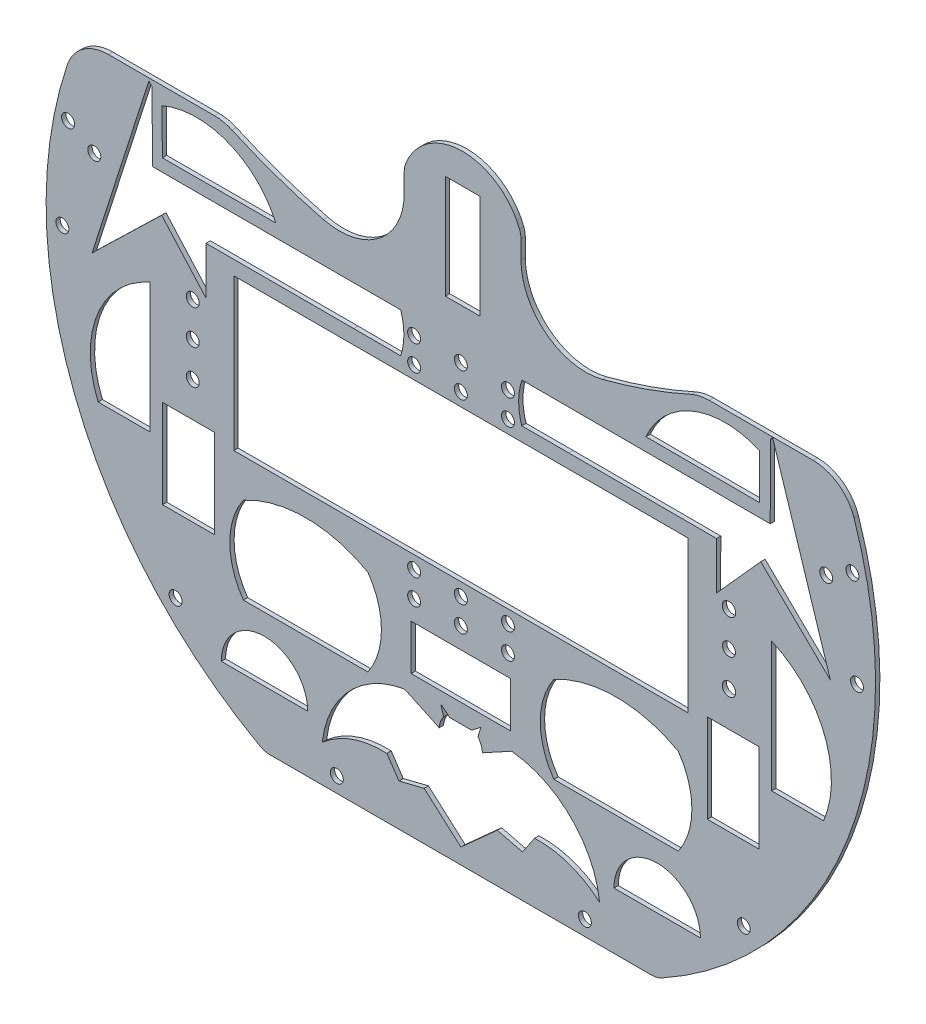
SolidWorks part; units mm, degrees
ref_plane "Alzado" through (0, 0, 0) normal (0, 0, 1) x (1, 0, 0)
ref_plane "Planta" through (0, 0, 0) normal (0, 1, 0) x (1, 0, 0)
ref_plane "Vista lateral" through (0, 0, 0) normal (1, 0, 0) x (0, 0, -1)
sketch "Croquis1" plane through (0, 0, 0) normal (0, 0, 1) x (1, 0, 0)
  line L6 (309.5147, 61.7075) -> (309.5147, 57.3276)
  line L7 (336.5145, 61.7075) -> (336.5145, 57.5364)
  line L8 (253.593, 36.515) -> (253.4846, 46.9134)
  line L9 (251.233, 49.5222) -> (250.4719, 50.3729)
  line L10 (253.593, 36.515) -> (279.8125, 36.577)
  line L11 (394.2079, 50.4438) -> (394.7077, 51.0653)
  line L12 (265.656, 50.9799) -> (241.0817, 50.9799)
  line L13 (391.6231, 36.515) -> (391.7315, 46.9134)
  line L14 (391.6231, 36.515) -> (365.4036, 36.577)
  line L15 (380.0087, 51.1814) -> (404.0672, 51.1814)
  line L111 (253.6081, -32.9371) -> (259.6081, -32.9371)
  line L112 (259.6081, -32.9371) -> (265.6081, -32.9371)
  line L113 (265.6081, -32.9371) -> (265.6081, -12.4371)
  line L114 (265.6081, -12.4371) -> (253.6081, -12.4371)
  line L115 (253.6081, -12.4371) -> (253.6081, -32.9371)
  line L116 (391.6081, -22.6871) -> (391.6081, -12.4371)
  line L117 (391.6081, -22.6871) -> (391.6081, -32.9371)
  line L118 (391.6081, -32.9371) -> (379.6081, -32.9371)
  line L119 (379.6081, -32.9371) -> (379.6081, -12.4371)
  line L120 (379.6081, -12.4371) -> (391.6081, -12.4371)
  line L121 (311.1081, -38.0079) -> (334.1081, -38.0079)
  line L122 (327.0147, 41.5355) -> (327.0147, 65.5355)
  line L123 (327.0147, 65.5355) -> (319.0147, 65.5355)
  line L124 (319.0147, 65.5355) -> (319.0147, 41.5355)
  line L125 (283.6081, 21.1487) -> (361.6081, 21.1487)
  line L126 (319.0147, 41.5355) -> (327.0147, 41.5355)
  line L127 (283.6081, 21.1487) -> (272.6081, 21.1487)
  line L128 (361.6081, 21.1487) -> (372.6081, 21.1487)
  line L129 (272.6081, 21.1487) -> (272.3081, 21.1487)
  line L132 (372.9081, -42.6871) -> (344.1081, -42.6871)
  line L133 (301.1081, -42.6871) -> (272.3081, -42.6871)
  line L136 (372.9081, -13.8513) -> (375.1081, -13.8513)
  line L137 (375.1081, -13.8513) -> (375.1081, 21.1487)
  line L138 (372.6081, 21.1487) -> (375.1081, 21.1487)
  line L139 (272.3081, -13.8513) -> (270.1081, -13.8513)
  line L140 (270.1081, -13.8513) -> (270.1081, 21.1487)
  line L141 (270.1081, 21.1487) -> (272.6081, 21.1487)
  line L142 (311.1081, -27.5079) -> (311.1081, -38.0079)
  line L143 (334.1081, -27.5079) -> (334.1081, -38.0079)
  line L144 (270.1081, -13.8513) -> (270.1081, 21.1487)
  line L147 (272.3081, -13.8513) -> (372.9081, -13.8513)
  line L148 (311.1081, -27.5079) -> (334.1081, -27.5079)
  line L149 (322.6081, -67.0079) -> (314.1156, -59.4845)
  line L150 (322.6081, -67.0079) -> (331.0395, -59.4162)
  line L151 (331.0395, -59.4162) -> (336.8613, -60.8677)
  line L152 (336.8613, -60.8677) -> (339.6572, -56.7225)
  line L153 (308.2939, -60.936) -> (305.4979, -56.7908)
  line L154 (322.6081, -42.3598) -> (320.1081, -42.3598)
  line L155 (322.6081, -42.3598) -> (325.1081, -42.3598)
  line L156 (325.1081, -42.3598) -> (327.2548, -40.6826)
  line L157 (327.2548, -40.6826) -> (326.5733, -42.9116)
  line L158 (327.2548, -40.6826) -> (326.5711, -42.9186)
  line L159 (320.1081, -42.3598) -> (317.9614, -40.6826)
  line L160 (317.9614, -40.6826) -> (318.6428, -42.9116)
  line L161 (317.9614, -40.6826) -> (318.645, -42.9186)
  line L162 (317.6081, -45.6294) -> (309.5758, -41.866)
  line L163 (327.6081, -45.6294) -> (334.3613, -41.9345)
  line L164 (314.1156, -59.4845) -> (308.2939, -60.936)
  line L165 (251.233, 49.5222) -> (251.2592, 33.6206)
  line L166 (297.8512, 24.4503) -> (263.6769, 24.4503)
  line L167 (263.6769, 24.4503) -> (263.6769, 13.4789)
  line L168 (263.6769, 13.4789) -> (253.4246, 24.9379)
  line L169 (253.4246, 24.9379) -> (237.3248, 9.3342)
  line L170 (237.3248, 9.3342) -> (250.4719, 50.3729)
  line L171 (297.8353, 33.6206) -> (251.2592, 33.6206)
  line L172 (308.7015, 24.4226) -> (297.8512, 24.4503)
  line L173 (297.8353, 33.6206) -> (308.7015, 33.6206)
  line L174 (394.2079, 50.4438) -> (394.1514, 33.5004)
  line L175 (347.5441, 24.4085) -> (381.7183, 24.351)
  line L176 (381.7183, 24.351) -> (381.6999, 13.3796)
  line L177 (381.6999, 13.3796) -> (391.9714, 24.8213)
  line L178 (391.9714, 24.8213) -> (408.0449, 9.1905)
  line L179 (408.0449, 9.1905) -> (394.7077, 51.0653)
  line L180 (347.5754, 33.5788) -> (394.1514, 33.5004)
  line L181 (336.6937, 24.399) -> (347.5441, 24.4085)
  line L182 (347.5754, 33.5788) -> (336.7092, 33.5971)
  line L183 (267.2015, -57.5079) -> (287.2015, -57.5079)
  line L184 (378.0147, -57.5079) -> (358.0147, -57.5079)
  line L185 (293.9244, -70.6013) -> (366.6962, -70.6013)
  line L186 (293.9244, -70.6013) -> (278.52, -70.6013)
  line L187 (394.4844, -19.815) -> (406.4844, -19.815)
  line L188 (394.4844, -19.815) -> (394.4844, 10.185)
  line L189 (250.7317, -19.815) -> (238.7317, -19.815)
  line L190 (250.7317, -19.815) -> (250.7317, 10.185)
  arc A2 (309.8507, 63.5097) -> (336.1785, 63.5097) centre (323.0146, 58.4231) cw
  arc A8 (269.7373, 50.1091) -> (290.8357, 42.7857) centre (322.6081, 168.3733) ccw
  arc A9 (355.2999, 43.0219) -> (375.8953, 50.2962) centre (322.6081, 168.3733) ccw
  arc A10 (336.5145, 57.5364) -> (355.2999, 43.0219) centre (351.5145, 57.5364) ccw
  arc A11 (309.5147, 57.3276) -> (290.8357, 42.7857) centre (294.5147, 57.3276) cw
  arc A12 (365.4036, 36.577) -> (391.7315, 46.9134) centre (383.7357, 28.5812) cw
  arc A13 (279.8125, 36.577) -> (253.4846, 46.9134) centre (261.4804, 28.5812) ccw
  arc A16 (369.1211, -69.9739) -> (366.6962, -70.6013) centre (366.6962, -65.6013) cw
  arc A17 (278.52, -70.6013) -> (276.0951, -69.9739) centre (278.52, -65.6013) cw
  arc A18 (336.1785, 63.5097) -> (336.5145, 61.7075) centre (331.5145, 61.7075) cw
  arc A19 (309.8507, 63.5097) -> (309.5147, 61.7075) centre (314.5147, 61.7075) ccw
  arc A22 (269.7373, 50.1091) -> (265.656, 50.9799) centre (265.656, 40.9799) ccw
  arc A23 (380.0087, 51.1814) -> (375.8953, 50.2962) centre (380.0087, 41.1814) ccw
  arc A24 (413.5495, 44.3573) -> (404.0672, 51.1814) centre (404.0672, 41.1814) ccw
  arc A25 (241.0817, 50.9799) -> (231.5915, 44.1323) centre (241.0817, 40.9799) ccw
  circle A159 centre (333.5054, 29.9987) radius 1.5
  circle A164 centre (384.6081, -4.3513) radius 1.55
  circle A165 centre (384.6081, 11.6487) radius 1.55
  circle A166 centre (293.9244, -67.1013) radius 1.5
  circle A167 centre (351.292, -67.1013) radius 1.5
  circle A168 centre (237.8501, 29.5597) radius 1.5
  circle A169 centre (407.0983, 29.6722) radius 1.5
  arc A170 (231.5915, 44.1323) -> (276.0951, -69.9739) centre (322.6081, 13.8987) ccw
  arc A171 (369.1211, -69.9739) -> (413.5495, 44.3573) centre (322.6081, 13.8987) ccw
  circle A176 centre (311.8064, 29.9987) radius 1.5
  circle A177 centre (260.6081, 11.6487) radius 1.5
  circle A178 centre (260.6081, -4.3513) radius 1.5
  circle A179 centre (260.6081, 3.6487) radius 1.5
  circle A180 centre (384.6081, 3.6487) radius 1.5
  circle A182 centre (231.7879, 33.0597) radius 1.5
  circle A184 centre (413.1604, 33.1722) radius 1.5
  circle A185 centre (414.2216, 11.3987) radius 1.5
  circle A186 centre (256.6409, -50.1013) radius 1.5
  circle A187 centre (388.037, -50.1013) radius 1.5
  circle A188 centre (322.6081, 29.9987) radius 1.5
  circle A189 centre (311.8064, -22.7013) radius 1.5
  circle A190 centre (322.6081, -22.7013) radius 1.5
  circle A191 centre (333.5054, -22.7013) radius 1.5
  circle A192 centre (322.6081, -16.8513) radius 1.5
  circle A193 centre (311.8064, -16.8513) radius 1.5
  circle A194 centre (333.5054, -16.8513) radius 1.5
  circle A195 centre (311.8064, 24.1487) radius 1.5
  circle A196 centre (322.6081, 24.1487) radius 1.5
  circle A197 centre (333.5054, 24.1487) radius 1.5
  arc A204 (354.7015, -62.0505) -> (334.3613, -41.9345) centre (332.0867, -64.5759) ccw
  arc A205 (309.5758, -41.866) -> (290.5747, -62.0505) centre (313.4787, -64.5759) ccw
  arc A206 (305.4979, -56.7908) -> (290.5747, -62.0505) centre (304.5304, -77.8464) ccw
  arc A207 (354.7015, -62.0505) -> (339.6572, -56.7225) centre (340.6905, -77.7086) ccw
  arc A208 (318.645, -42.9186) -> (317.6081, -45.6294) centre (322.6081, -45.9883) ccw
  arc A209 (327.6081, -45.6294) -> (326.5711, -42.9186) centre (322.6081, -45.9883) ccw
  arc A210 (272.3081, -22.6871) -> (272.3081, -42.6871) centre (286.7081, -32.6871) ccw
  arc A211 (301.1081, -42.6871) -> (301.1081, -22.6871) centre (286.7081, -32.6871) ccw
  arc A212 (344.1081, -22.6871) -> (344.1081, -42.6871) centre (358.5081, -32.6871) ccw
  arc A213 (372.9081, -42.6871) -> (372.9081, -22.6871) centre (358.5081, -32.6871) ccw
  arc A222 (301.1081, -22.6871) -> (272.3081, -22.6871) centre (286.7081, -48.8068) ccw
  arc A223 (372.9081, -22.6871) -> (344.1081, -22.6871) centre (358.5081, -48.8068) ccw
  arc A224 (287.2015, -57.5079) -> (267.2015, -57.5079) centre (277.2015, -57.5079) ccw
  arc A225 (378.0147, -57.5079) -> (358.0147, -57.5079) centre (368.0147, -57.5079) ccw
  circle A226 centre (230.4564, 11.3987) radius 1.5
  arc A227 (308.7015, 24.4226) -> (308.7015, 33.6206) centre (294.7373, 29.0216) ccw
  arc A228 (336.7287, 33.597) -> (336.6937, 24.399) centre (350.6656, 28.9451) ccw
  arc A229 (406.4844, -19.815) -> (394.4844, 10.185) centre (385.3631, -10.8636) ccw
  arc A230 (250.7317, 10.185) -> (238.7317, -19.815) centre (259.8531, -10.8636) ccw
  point P56 (0, 0)
extrude "Saliente-Extruir1" add sketch "Croquis1" along normal blind 1
